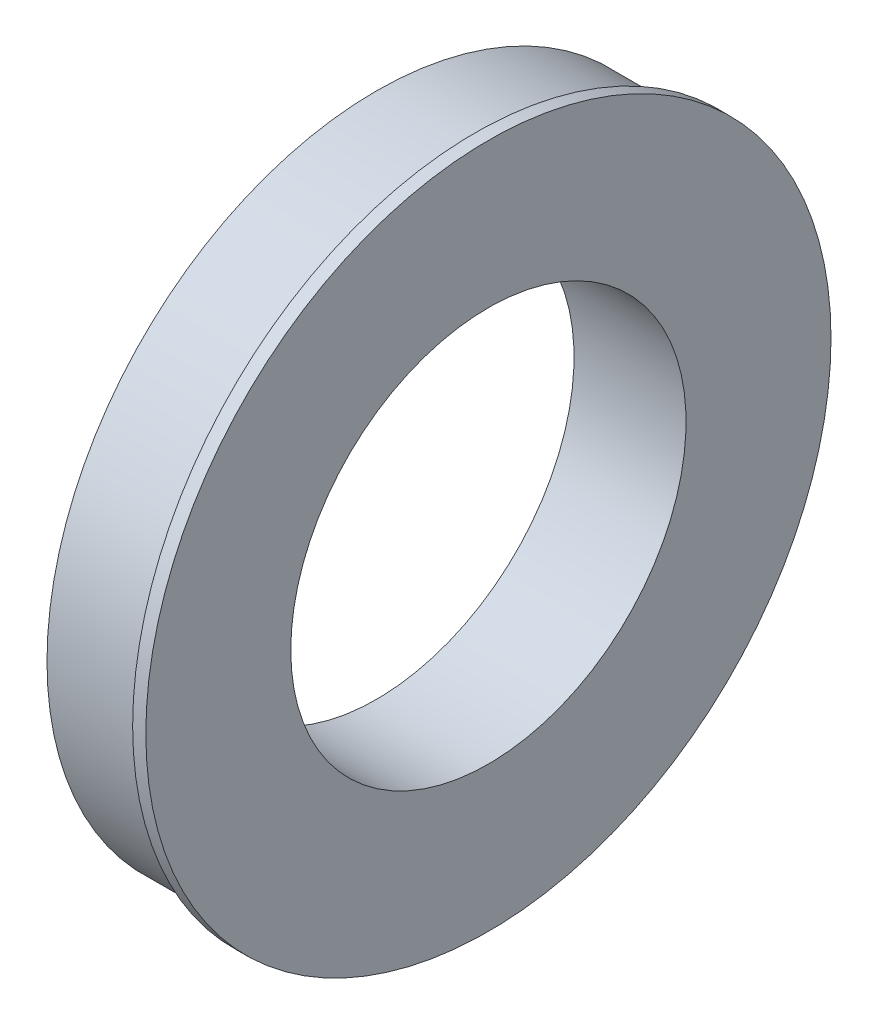
SolidWorks part; units mm, degrees
ref_plane "Front Plane" through (0, 0, 0) normal (0, 0, 1) x (1, 0, 0)
ref_plane "Top Plane" through (0, 0, 0) normal (0, 1, 0) x (1, 0, 0)
ref_plane "Right Plane" through (0, 0, 0) normal (1, 0, 0) x (0, 0, -1)
sketch "Sketch1" plane through (0, 0, 0) normal (1, 0, 0) x (0, 0, -1)
  circle A0 centre (0, 0) radius 38.1
  circle A1 centre (0, 0) radius 63.5
  dimension "D1" = 76.2
  dimension "D2" = 127
extrude "Boss-Extrude1" add sketch "Sketch1" along normal blind 19.05
sketch "Sketch2" plane through (19.05, 0, 0) normal (1, 0, 0) x (0, 0, -1)
  circle A1 centre (0, 0) radius 38.1 construction
  circle A2 centre (0, 0) radius 66.04
  circle A3 centre (0, 0) radius 66.04
  circle A4 centre (0, 0) radius 38.1
  dimension "D1" = 2.54
extrude "Boss-Extrude2" add sketch "Sketch2" along normal blind 2.54
scale "Scale1" scale about centroid uniform scaling yes scale factor 0.111317
